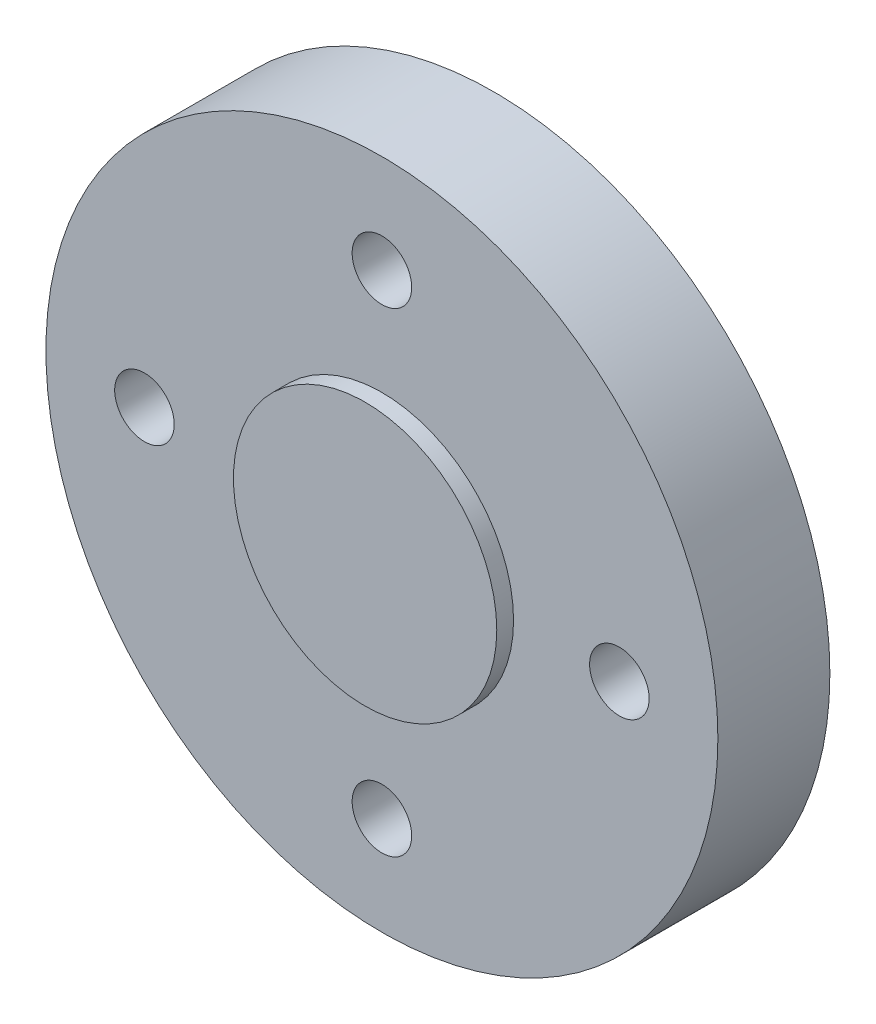
SolidWorks part; units mm, degrees
ref_plane "Front Plane" through (0, 0, 0) normal (0, 0, 1) x (1, 0, 0)
ref_plane "Top Plane" through (0, 0, 0) normal (0, 1, 0) x (1, 0, 0)
ref_plane "Right Plane" through (0, 0, 0) normal (1, 0, 0) x (0, 0, -1)
sketch "Sketch1" plane through (0, 0, 0) normal (0, 0, 1) x (1, 0, 0)
  circle A0 centre (0, 0) radius 30
  dimension "D1" = 60
extrude "Boss-Extrude1" add sketch "Sketch1" along normal blind 10
sketch "Sketch2" plane through (0, 0, 10) normal (0, 0, 1) x (1, 0, 0)
  circle A0 centre (0, 0) radius 11.756
extrude "Boss-Extrude3" add sketch "Sketch2" along normal mid plane 3
sketch "Sketch5" plane through (0, 0, 10) normal (0, 0, 1) x (1, 0, 0)
  line L0 (0.7079, -32.21) -> (0, -31.62) construction
  circle A0 centre (0, -21.2034) radius 2.6583
  circle A1 centre (-21.2034, 0) radius 2.6583
  circle A2 centre (0, 21.2034) radius 2.6583
  circle A3 centre (21.2034, 0) radius 2.6583
  point P13 (0, 0)
  dimension "D1" = 4
extrude "Cut-Extrude4" cut sketch "Sketch5" against normal blind 26
sketch "Sketch6" plane through (0, 0, 0) normal (0, 0, -1) x (-1, 0, 0)
  circle A0 centre (0, 0) radius 10.6342
extrude "Cut-Extrude5" cut sketch "Sketch6" against normal blind 9.5
